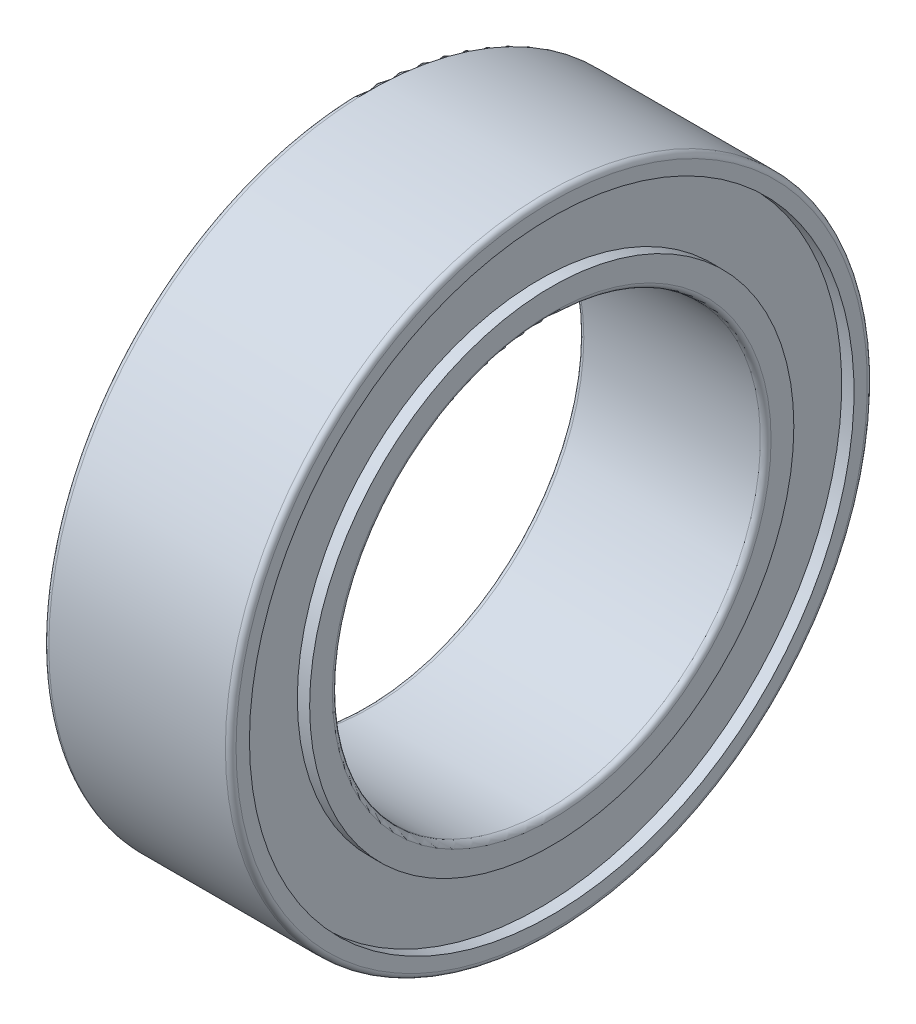
SolidWorks part; units mm, degrees
ref_plane "Front Plane" through (0, 0, 0) normal (0, 0, 1) x (1, 0, 0)
ref_plane "Top Plane" through (0, 0, 0) normal (0, 1, 0) x (1, 0, 0)
ref_plane "Right Plane" through (0, 0, 0) normal (1, 0, 0) x (0, 0, -1)
sketch "Sketch1" plane through (0, 0, 0) normal (0, 0, 1) x (1, 0, 0)
  line L0 (0, 0) -> (3.5, 0) construction
  line L1 (0, 4) -> (3.5, 4)
  line L2 (0, 6) -> (3.5, 6)
  line L3 (0, 6) -> (0, 5.65)
  line L4 (0, 5.65) -> (0.23, 5.65)
  line L5 (3.5, 6) -> (3.5, 5.65)
  line L6 (0.23, 5.65) -> (0.23, 4.525)
  line L7 (0.23, 4.525) -> (0, 4.525)
  line L8 (0, 4.525) -> (0, 4)
  line L9 (3.5, 5.65) -> (3.27, 5.65)
  line L10 (3.27, 5.65) -> (3.27, 4.525)
  line L11 (3.27, 4.525) -> (3.5, 4.525)
  line L12 (3.5, 4.525) -> (3.5, 4)
  dimension "D" = 12
  dimension "B" = 3.5
  dimension "D_s" = 8
  dimension "MSM_1" = 11.3
  dimension "MSM_2" = 9.05
  dimension "MSM_3" = 0.23
revolve "Revolve1" add sketch "Sketch1" angle 360 about L0
fillet "Fillet1" radius 0.1 2 edges at (3.5, 0, 6) (0, 0, 6)
fillet "Fillet2" radius 0.1 2 edges at (3.5, 0, 4) (0, 0, 4)
